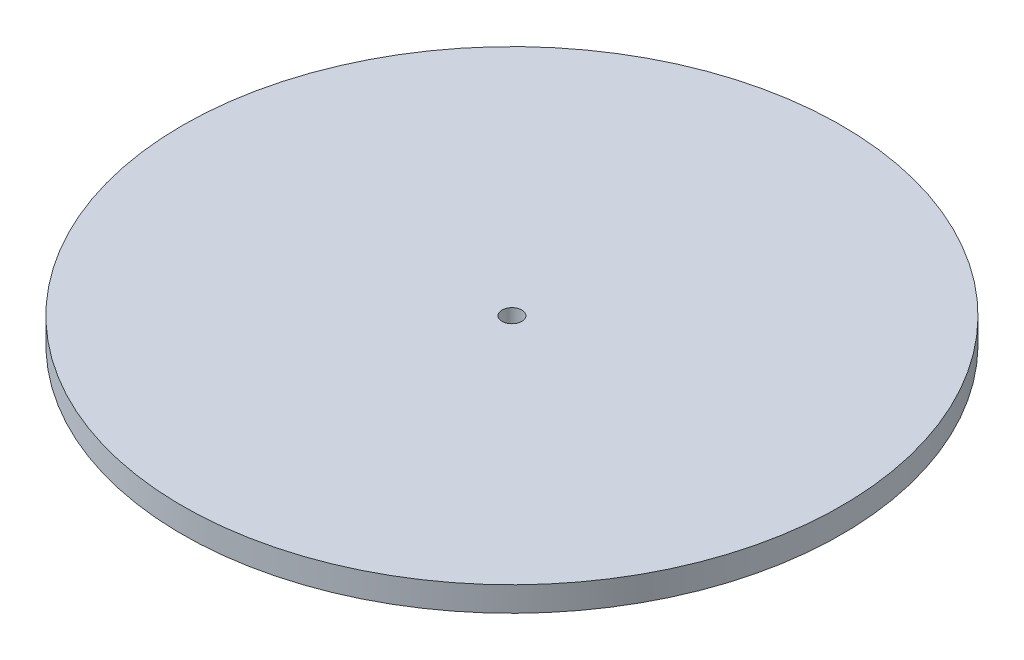
SolidWorks part; units mm, degrees
ref_plane "Front Plane" through (0, 0, 0) normal (0, 0, 1) x (1, 0, 0)
ref_plane "Top Plane" through (0, 0, 0) normal (0, 1, 0) x (1, 0, 0)
ref_plane "Right Plane" through (0, 0, 0) normal (1, 0, 0) x (0, 0, -1)
sketch "Sketch3" plane through (0, 0, 0) normal (0, 0, 1) x (1, 0, 0)
  line L0 (37, 12.3258) -> (37, 16.3258) construction
  line L1 (37, 16.3258) -> (0, 16.3258) construction
  line L2 (0, 16.3258) -> (0, 0) construction
  line L4 (1.2, 16.3258) -> (1.2, 11.3258)
  line L5 (1.2, 11.3258) -> (0, 11.3258)
  line L6 (0, 11.3258) -> (0, 0)
  line L7 (37, 12.3258) -> (40, 12.3258) construction
  line L8 (40, 12.3258) -> (40, 16.3258) construction
  line L9 (40, 16.3258) -> (1.2, 16.3258)
  line L10 (37, 12.3258) -> (37, 13.3258)
  line L11 (37, 13.3258) -> (40, 13.3258)
  line L12 (40, 13.3258) -> (40, 16.3258)
  spline S0 degree 8 poles (-3.7, 0.3743) (1.8482, -0.7159) (7.3965, -0.1391) (12.9447, 3.6706) (18.493, 4.4307) (24.0412, 7.8473) (29.5895, 9.2924) (35.1377, 11.7784) (40.686, 13.6456) knots 0 0 0 0 0 0 0 0 0 1 1 1 1 1 1 1 1 1 construction
  spline S1 degree 8 poles (0, 0) (4.625, -0.015) (9.25, 1.244) (13.875, 3.4574) (18.5, 4.9496) (23.125, 7.0862) (27.75, 8.7808) (32.375, 10.6068) (37, 12.3258) knots 0.08336 0.08336 0.08336 0.08336 0.08336 0.08336 0.08336 0.08336 0.08336 0.916956 0.916956 0.916956 0.916956 0.916956 0.916956 0.916956 0.916956 0.916956
  dimension "D1" = 3
  dimension "D2" = 1.2
  dimension "D3" = 5
  dimension "D4" = 3
  dimension "D5" = 40
  dimension "D6" = 12.3258
  dimension "D7" = 37
  dimension "D8" = 4
revolve "Revolve4" add sketch "Sketch3" angle 360 about L2
sketch "Sketch5" plane through (0, 16.3258, 0) normal (0, 1, 0) x (1, 0, 0)
  circle A0 centre (0, 0) radius 1.2
  circle A2 centre (0, 0) radius 1.2 construction
extrude "Cut-Extrude1" cut sketch "Sketch5" against normal through all
